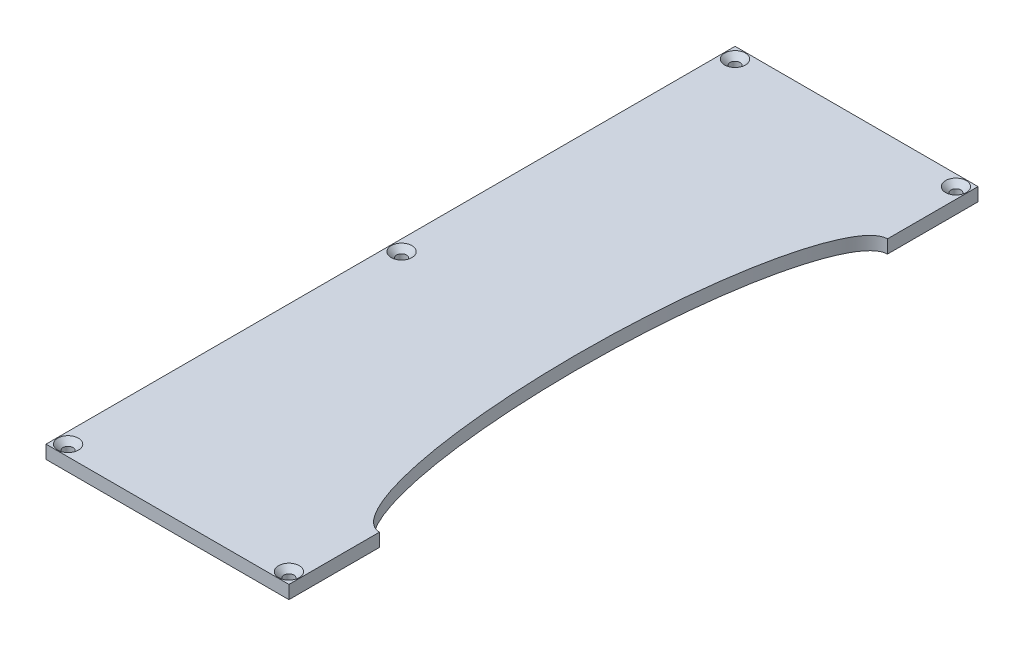
SolidWorks part; units mm, degrees
ref_plane "Front Plane" through (0, 0, 0) normal (0, 0, 1) x (1, 0, 0)
ref_plane "Top Plane" through (0, 0, 0) normal (0, 1, 0) x (1, 0, 0)
ref_plane "Right Plane" through (0, 0, 0) normal (1, 0, 0) x (0, 0, -1)
sketch "Sketch1" plane through (0, 0, 0) normal (0, 1, 0) x (1, 0, 0)
  line L0 (0, 115) -> (0, 156)
  line L1 (0, 156) -> (-110, 156)
  line L2 (-110, 156) -> (-110, -156)
  line L3 (-110, -156) -> (0, -156)
  line L4 (0, -156) -> (0, -115)
  ellipse E0 centre (0, 0) end of major axis (0, 115) minor radius 25
  dimension "D1" = 230
  dimension "D2" = 50
  dimension "D3" = 156
  dimension "D4" = 312
  dimension "D5" = 110
extrude "Boss-Extrude1" add sketch "Sketch1" along normal blind 6 contours E0 L4 L3 L2 L1 L0
sketch "Sketch2" plane through (0, 6, 0) normal (0, 1, 0) x (1, 0, 0)
  line L0 (-110, -156) -> (0, -156) construction
  line L1 (0, -156) -> (0, -115) construction
  line L2 (-110, 156) -> (-110, -156) construction
  line L3 (0, 156) -> (-110, 156) construction
  point P0 (-105, 151)
  point P1 (-5, -151)
  point P10 (-5, 151)
  point P11 (-105, -151)
  point P12 (-105, 0)
  dimension "D1" = 5
  dimension "D2" = 5
  dimension "D3" = 5
  dimension "D4" = 5
hole_wizard "CSK for M4 Countersunk Flat Head Screw1" positions "Sketch3" profile "Sketch4" countersink size "M4" standard "ISO"
sketch "Sketch3" plane through (0, 6, 0) normal (0, 1, 0) x (1, 0, 0)
  point P0 (-105, 151)
  point P3 (-5, 151)
  point P6 (-5, -151)
  point P9 (-105, -151)
  point P13 (-105, 0)
sketch "Sketch4" plane through (-105, 6, -151) normal (1, 0, 0) x (0, 0, 1)
  line L0 (0, 0) -> (0, 11.3519)
  line L1 (0, 11.3519) -> (2.25, 10)
  line L2 (2.25, 10) -> (2.25, 2.45)
  line L3 (2.25, 2.45) -> (4.7, 0)
  line L5 (4.7, 0) -> (0, 0)
  line L6 (-2.25, 2.45) -> (-4.7, 0) construction
  line L10 (0, 11.3519) -> (-2.25, 10) construction
  line L11 (0, -6.35) -> (0, 107.95) construction
  dimension "Hole Dia." = 4.5
  dimension "Hole Depth" = 10
  dimension "Near C'Sink Dia." = 9.4
  dimension "Near C'Sink Angle" = 90
  dimension "Drill Angle" = 118
